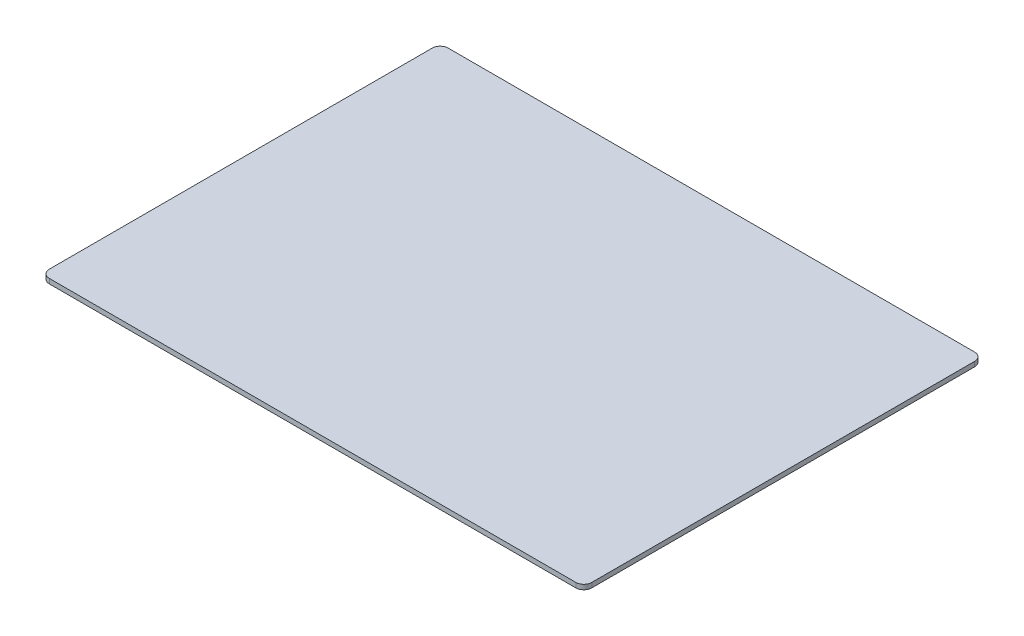
SolidWorks part; units mm, degrees
ref_plane "前视基准面" through (0, 0, 0) normal (0, 0, 1) x (1, 0, 0)
ref_plane "上视基准面" through (0, 0, 0) normal (0, 1, 0) x (1, 0, 0)
ref_plane "右视基准面" through (0, 0, 0) normal (1, 0, 0) x (0, 0, -1)
sketch "草图2" plane through (0, 0, 0) normal (0, 1, 0) x (1, 0, 0)
  line L1 (-165, 125) -> (165, 125)
  line L2 (-170, 120) -> (-170, -120)
  line L3 (-165, -125) -> (165, -125)
  line L4 (170, 120) -> (170, -120)
  line L5 (-170, 125) -> (170, -125) construction
  line L6 (-170, -125) -> (170, 125) construction
  arc A0 (-165, -125) -> (-170, -120) centre (-165, -120) cw
  arc A1 (170, -120) -> (165, -125) centre (165, -120) cw
  arc A2 (170, 120) -> (165, 125) centre (165, 120) ccw
  arc A3 (-165, 125) -> (-170, 120) centre (-165, 120) ccw
  point P0 (0, 0)
  dimension "D1" = 5
extrude "凸台-拉伸1" add sketch "草图2" along normal blind 3
